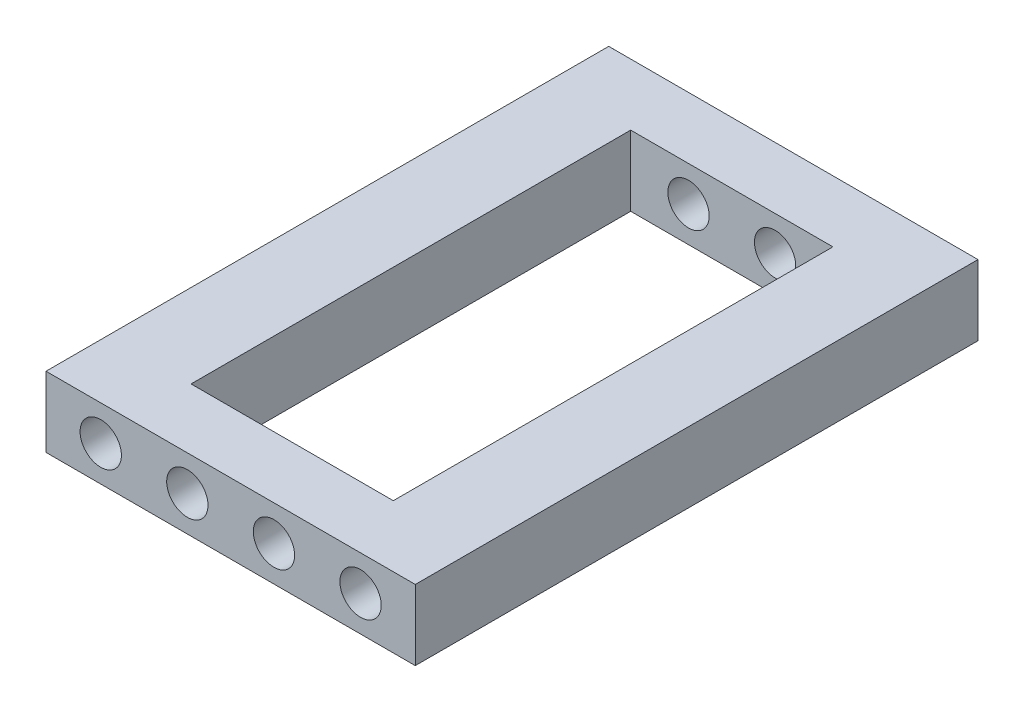
SolidWorks part; units mm, degrees
ref_plane "前视基准面" through (0, 0, 0) normal (0, 0, 1) x (1, 0, 0)
ref_plane "上视基准面" through (0, 0, 0) normal (0, 1, 0) x (1, 0, 0)
ref_plane "右视基准面" through (0, 0, 0) normal (1, 0, 0) x (0, 0, -1)
sketch "草图1" plane through (0, 0, 0) normal (0, 0, 1) x (1, 0, 0)
  line L0 (0, -55) -> (0, 55) construction
  line L1 (-21, -4) -> (21, -4)
  line L2 (-21, -4) -> (-21, 4)
  line L3 (-21, 4) -> (21, 4)
  line L4 (21, -4) -> (21, 4)
  line L5 (-21, -4) -> (21, 4) construction
  line L6 (-21, 4) -> (21, -4) construction
  circle A0 centre (-4.925, 0) radius 2.35
  circle A1 centre (4.925, 0) radius 2.35
  circle A2 centre (-14.775, 0) radius 2.35
  circle A3 centre (14.775, 0) radius 2.35
  point P0 (0, 0)
  dimension "D2" = 4.7
  dimension "D3" = 9.85
  dimension "D4" = 4.7
  dimension "D5" = 9.85
  dimension "D1" = 42
  dimension "D6" = 8
extrude "凸台-拉伸1" add sketch "草图1" along normal mid plane 64
sketch "草图2" plane through (0, 4, 0) normal (0, 1, 0) x (1, 0, 0)
  line L0 (-4.4, 0) -> (4.4, 0) construction
  line L5 (-11.5, -25) -> (11.5, -25)
  line L6 (-11.5, -25) -> (-11.5, -5)
  line L7 (-11.5, -5) -> (11.5, -5)
  line L8 (11.5, -25) -> (11.5, -5)
  line L9 (-11.5, -25) -> (11.5, -5) construction
  line L10 (-11.5, -5) -> (11.5, -25) construction
  line L11 (-11.5, 5) -> (11.5, 25) construction
  line L12 (-11.5, 25) -> (11.5, 5) construction
  line L13 (11.5, 25) -> (11.5, 5)
  line L14 (-11.5, 5) -> (11.5, 5)
  line L15 (-11.5, 25) -> (-11.5, 5)
  line L16 (-11.5, 25) -> (11.5, 25)
  point P0 (0, -15)
  point P12 (0, 15)
  dimension "D1" = 23
  dimension "D2" = 15
  dimension "D3" = 20
extrude "切除-拉伸2" cut sketch "草图2" against normal blind 14
sketch "草图3" plane through (0, 4, 0) normal (0, 1, 0) x (1, 0, 0)
  line L0 (11.5, 5) -> (11.5, 25) construction
  line L1 (-11.5, -13.5912) -> (11.5, -13.5912)
  line L2 (-11.5, -13.5912) -> (-11.5, 13.5912)
  line L3 (-11.5, 13.5912) -> (11.5, 13.5912)
  line L4 (11.5, -13.5912) -> (11.5, 13.5912)
  line L5 (-11.5, -13.5912) -> (11.5, 13.5912) construction
  line L6 (-11.5, 13.5912) -> (11.5, -13.5912) construction
  point P0 (0, 0)
extrude "切除-拉伸3" cut sketch "草图3" against normal blind 10
